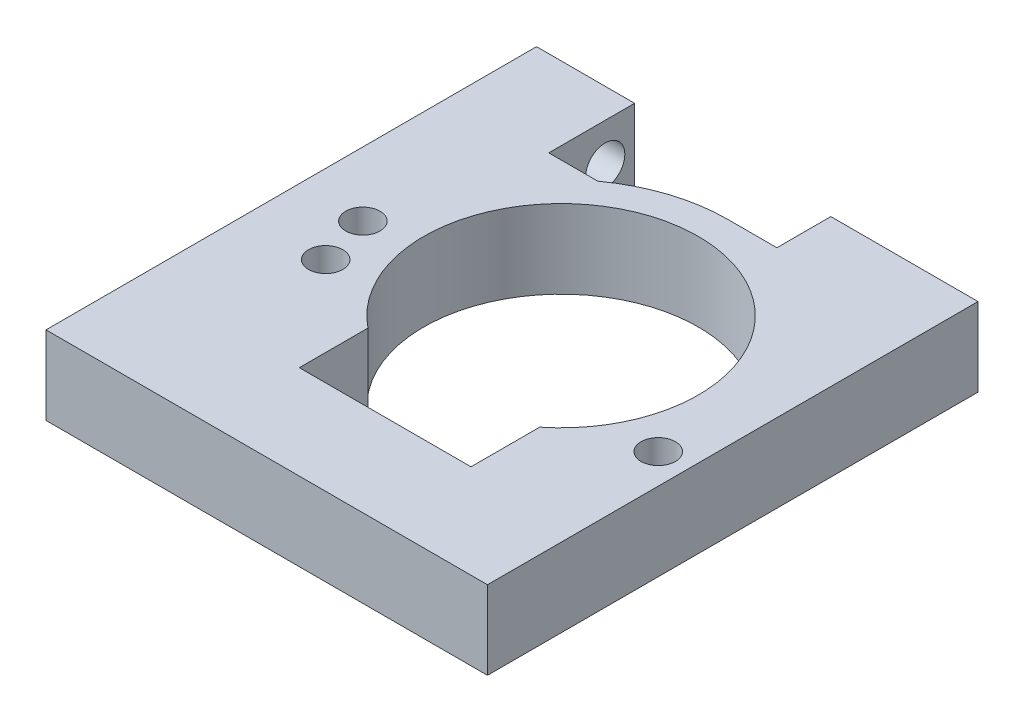
SolidWorks part; units mm, degrees
material "Acrylic (Medium-high impact)"
ref_plane "Front Plane" through (0, 0, 0) normal (0, 0, 1) x (1, 0, 0)
ref_plane "Top Plane" through (0, 0, 0) normal (0, 1, 0) x (1, 0, 0)
ref_plane "Right Plane" through (0, 0, 0) normal (1, 0, 0) x (0, 0, -1)
sketch "Sketch1" plane through (0, 0, 0) normal (0, 1, 0) x (1, 0, 0)
  line L0 (0, 0) -> (-18.45, 0) construction
  line L1 (8.75, -17.9287) -> (8.75, -10.9287)
  line L2 (-8.75, -17.9287) -> (-8.75, -10.9287)
  line L3 (-8.75, -17.9287) -> (8.75, -17.9287)
  line L4 (0, 0) -> (18.45, 0) construction
  line L5 (18.45, -1.75) -> (18.45, -7.0415) construction
  line L6 (18.45, -7.0415) -> (16.95, -7.0415) construction
  line L7 (-18.45, -1.75) -> (-18.45, -7.0415) construction
  line L8 (-18.45, -7.0415) -> (-16.95, -7.0415) construction
  arc A0 (8.75, -10.9287) -> (-8.75, -10.9287) centre (0, 0) ccw
  circle A1 centre (0, 8) radius 2.5 construction
  circle A2 centre (18.45, -1.75) radius 1.75 construction
  circle A3 centre (-18.45, -1.75) radius 1.75
  circle A4 centre (16.95, -7.0415) radius 1.75
  circle A5 centre (-16.95, -7.0415) radius 1.75
  dimension "D1" = 28
  dimension "D2" = 5
  dimension "D6" = 3.5
  dimension "D7" = 40.4
  dimension "D8" = 1.5
  dimension "D9" = 2
  dimension "D10" = 2
  dimension "D3" = 8
  dimension "D4" = 7
  dimension "D5" = 17.5
sketch "Sketch2" plane through (0, 0, 0) normal (0, 1, 0) x (1, 0, 0)
  line L0 (0, 0) -> (-25, 0) construction
  line L1 (-25, 22.5) -> (20, 22.5)
  line L2 (-25, 22.5) -> (-25, -27.5)
  line L3 (-25, -27.5) -> (20, -27.5)
  line L4 (20, 22.5) -> (20, -27.5)
  line L5 (0, 0) -> (20, 0) construction
  line L6 (0, 0) -> (0, 17.5) construction
  line L7 (0, 0) -> (0, -22.5) construction
  circle A0 centre (0, 8) radius 2.5 construction
  dimension "D5" = 5
  dimension "D1" = 45
  dimension "D2" = 50
  dimension "D3" = 17.5
  dimension "D4" = 8
  dimension "D6" = 9.5
  dimension "D7" = 25
  dimension "D8" = 20
  dimension "D9" = 22.5
extrude "Stepper Slider Boss-Extrude1" add sketch "Sketch2" against normal blind 8
extrude "Stepper Hole Cut-Extrude1" cut sketch "Sketch1" against normal up to surface (8 mm away) up to face at (-2.5, -8, 2.5)
sketch "Sketch3" plane through (0, 0, 0) normal (0, 1, 0) x (1, 0, 0)
  line L0 (0, 17) -> (0, 22.5) construction
  line L1 (20, 22.5) -> (-25, 22.5) construction
  line L2 (0, 22.5) -> (-15, 22.5)
  line L3 (-15, 22.5) -> (-15, 13.7477)
  line L5 (-15, 13.7477) -> (-10, 13.7477)
  line L6 (-25, 22.5) -> (-25, -27.5) construction
  line L7 (0, 17) -> (5, 17)
  line L9 (5, 17) -> (5, 22.5)
  line L10 (5, 22.5) -> (0, 22.5)
  line L11 (20, -27.5) -> (20, 22.5) construction
  arc A0 (-10, 13.7477) -> (0, 17) centre (0, 0) cw
  arc A1 (8.75, -10.9287) -> (-8.75, -10.9287) centre (0, 0) ccw construction
  dimension "D1" = 3
  dimension "D2" = 10
  dimension "D3" = 5
  dimension "D4" = 15
extrude "Adjusting Screw Pocket Cut-Extrude1" cut sketch "Sketch3" against normal up to surface (8 mm away) up to face at (-16.95, -8, 8.7915)
sketch "Sketch4" plane through (-15, 0, 0) normal (1, 0, 0) x (0, 0, -1)
  line L0 (22.5, -8) -> (22.5, 0) construction
  line L1 (22.5, 0) -> (13.7477, 0) construction
  circle A0 centre (19.5, -4) radius 2
  dimension "D3" = 4
  dimension "D1" = 3
  dimension "D2" = 4
extrude "Adjusting Screw Hole Cut-Extrude2" cut sketch "Sketch4" against normal up to surface (10 mm away) up to face at (-25, -4, 2.5)
